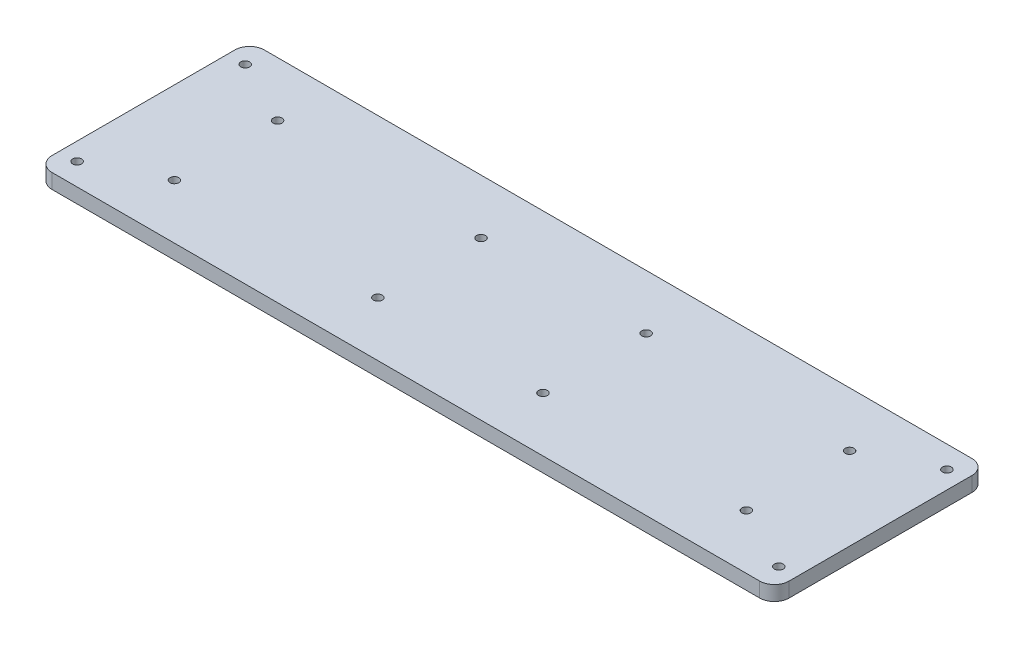
SolidWorks part; units mm, degrees
ref_plane "Front Plane" through (0, 0, 0) normal (0, 0, 1) x (1, 0, 0)
ref_plane "Top Plane" through (0, 0, 0) normal (0, 1, 0) x (1, 0, 0)
ref_plane "Right Plane" through (0, 0, 0) normal (1, 0, 0) x (0, 0, -1)
sketch "Sketch1" plane through (0, 0, 0) normal (0, 1, 0) x (1, 0, 0)
  line L0 (0, 36) -> (0, -36) construction
  line L1 (125, -36) -> (-125, -36)
  line L2 (125, -36) -> (125, 36)
  line L3 (125, 36) -> (-125, 36)
  line L4 (-125, -36) -> (-125, 36)
  line L5 (125, -36) -> (-125, 36) construction
  line L6 (125, 36) -> (-125, -36) construction
  line L7 (-125, 0) -> (125, 0) construction
  line L8 (-62.5, 21.5) -> (-62.5, -21.5) construction
  line L9 (-25, -21.5) -> (-100, -21.5) construction
  line L10 (-25, -21.5) -> (-25, 21.5) construction
  line L11 (-25, 21.5) -> (-100, 21.5) construction
  line L12 (-100, -21.5) -> (-100, 21.5) construction
  line L13 (-25, -21.5) -> (-100, 21.5) construction
  line L14 (-25, 21.5) -> (-100, -21.5) construction
  circle A0 centre (-119, -28.5) radius 1.5
  circle A1 centre (119, -28.5) radius 1.5
  circle A2 centre (119, 28.5) radius 1.5
  circle A3 centre (-119, 28.5) radius 1.5
  circle A4 centre (-97, 17.5) radius 1.5
  circle A5 centre (-97, -17.5) radius 1.5
  circle A6 centre (-28, 17.5) radius 1.5
  circle A7 centre (-28, -17.5) radius 1.5
  circle A8 centre (97, 17.5) radius 1.5
  circle A9 centre (97, -17.5) radius 1.5
  circle A10 centre (28, -17.5) radius 1.5
  circle A11 centre (28, 17.5) radius 1.5
  point P0 (0, 0)
  point P18 (-62.5, 0)
  dimension "D4" = 3
  dimension "D10" = 3
  dimension "D1" = 250
  dimension "D2" = 72
  dimension "D3" = 238
  dimension "D5" = 7.5
  dimension "D6" = 43
  dimension "D7" = 75
  dimension "D8" = 25
  dimension "D9" = 69
  dimension "D11" = 35
extrude "Boss-Extrude1" add sketch "Sketch1" along normal blind 5
fillet "Fillet1" radius 5 4 edges at (-125, 2.5, -36) (125, 2.5, -36) (125, 2.5, 36) (-125, 2.5, 36)
